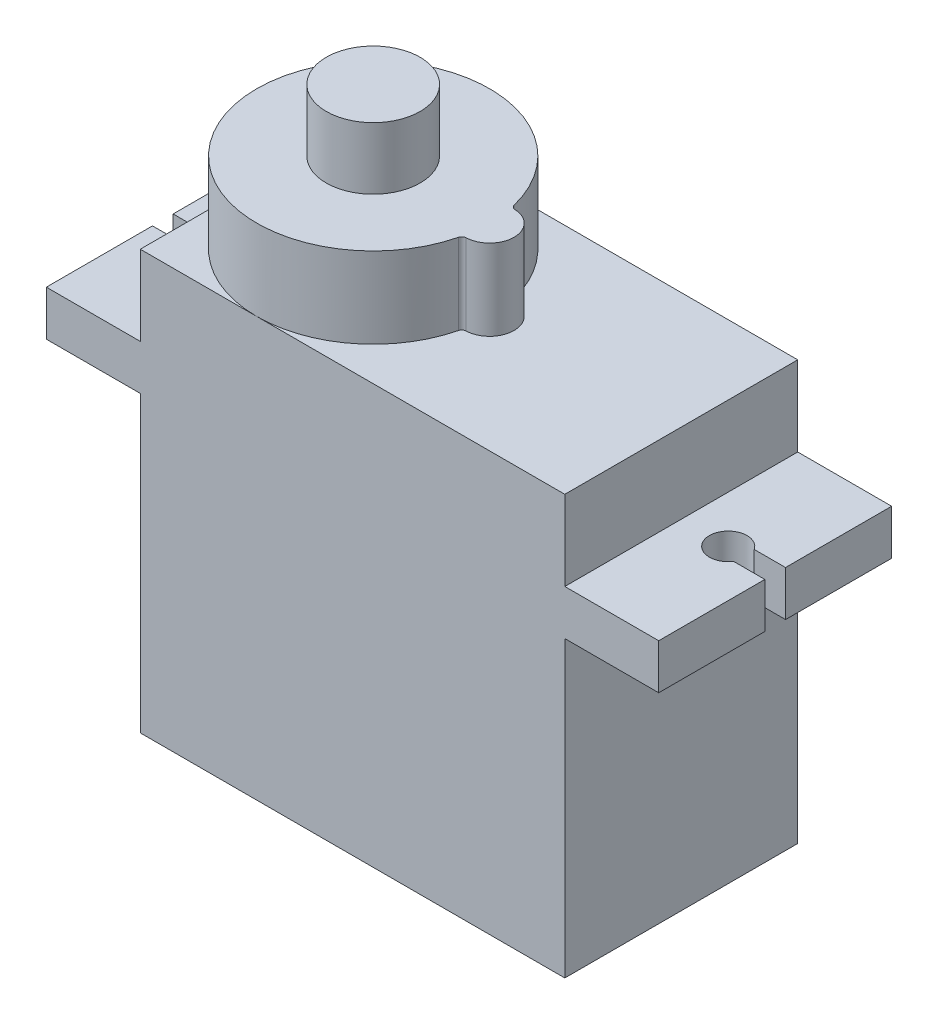
SolidWorks part; units mm, degrees
ref_plane "Front Plane" through (0, 0, 0) normal (0, 0, 1) x (1, 0, 0)
ref_plane "Top Plane" through (0, 0, 0) normal (0, 1, 0) x (1, 0, 0)
ref_plane "Right Plane" through (0, 0, 0) normal (1, 0, 0) x (0, 0, -1)
sketch "Sketch1" plane through (0, 0, 0) normal (0, 1, 0) x (1, 0, 0)
  line L1 (-11.3, 6.2) -> (11.3, 6.2)
  line L2 (-11.3, 6.2) -> (-11.3, -6.2)
  line L3 (-11.3, -6.2) -> (11.3, -6.2)
  line L4 (11.3, 6.2) -> (11.3, -6.2)
  line L5 (-11.3, 6.2) -> (11.3, -6.2) construction
  line L6 (-11.3, -6.2) -> (11.3, 6.2) construction
  point P0 (0, 0)
  dimension "D1" = 22.6
  dimension "D2" = 12.4
extrude "Boss-Extrude1" add sketch "Sketch1" along normal blind 22.3
sketch "Sketch2" plane through (0, 0, 6.2) normal (0, 0, 1) x (1, 0, 0)
  line L0 (11.3, 22.3) -> (11.3, 0) construction
  line L1 (16.3, 18.05) -> (11.3, 18.05)
  line L2 (16.3, 18.05) -> (16.3, 15.65)
  line L3 (16.3, 15.65) -> (11.3, 15.65)
  line L4 (11.3, 18.05) -> (11.3, 15.65)
  line L5 (16.3, 18.05) -> (11.3, 15.65) construction
  line L6 (16.3, 15.65) -> (11.3, 18.05) construction
  line L7 (-11.3, 22.3) -> (11.3, 22.3) construction
  line L8 (0, 0) -> (0, 14.975) construction
  line L9 (-16.3, 15.65) -> (-11.3, 18.05) construction
  line L10 (-16.3, 18.05) -> (-11.3, 15.65) construction
  line L11 (-11.3, 18.05) -> (-11.3, 15.65)
  line L12 (-16.3, 15.65) -> (-11.3, 15.65)
  line L13 (-16.3, 18.05) -> (-16.3, 15.65)
  line L14 (-16.3, 18.05) -> (-11.3, 18.05)
  point P0 (13.8, 16.85)
  point P16 (-13.8, 16.85)
  dimension "D1" = 4.25
  dimension "D2" = 2.4
  dimension "D3" = 5
extrude "Boss-Extrude2" add sketch "Sketch2" against normal up to vertex (12.4 mm away)
sketch "Sketch3" plane through (0, 18.05, 0) normal (0, 1, 0) x (1, 0, 0)
  line L0 (0, 0) -> (0, 25.3314) construction
  line L1 (0, 0) -> (13.8, 0) construction
  line L2 (14.6352, 0.55) -> (16.3, 0.55)
  line L3 (16.3, 6.2) -> (16.3, -6.2) construction
  line L4 (16.3, 0.55) -> (16.3, -0.55)
  line L5 (16.3, -0.55) -> (14.6352, -0.55)
  line L6 (-16.3, -0.55) -> (-14.6352, -0.55)
  line L7 (-16.3, 0.55) -> (-16.3, -0.55)
  line L8 (-14.6352, 0.55) -> (-16.3, 0.55)
  arc A0 (14.6352, 0.55) -> (14.6352, -0.55) centre (13.8, 0) ccw
  arc A1 (-14.6352, 0.55) -> (-14.6352, -0.55) centre (-13.8, 0) cw
  dimension "D1" = 2.5
  dimension "D3" = 2
  dimension "D2" = 1.1
extrude "Cut-Extrude1" cut sketch "Sketch3" against normal through all
sketch "Sketch4" plane through (0, 22.3, 0) normal (0, 1, 0) x (1, 0, 0)
  line L0 (-11.3, 6.2) -> (-11.3, -6.2) construction
  line L1 (11.3, 6.2) -> (-11.3, 6.2) construction
  arc A0 (0.9186, 1.4888) -> (0.9186, -1.4888) centre (-5.1, 0) ccw
  arc A1 (1.1514, -1.299) -> (1.1514, 1.299) centre (1.1, 0) ccw
  arc A2 (1.1514, -1.299) -> (0.9186, -1.4888) centre (1.1613, -1.5488) ccw
  arc A3 (1.1514, 1.299) -> (0.9186, 1.4888) centre (1.1613, 1.5488) cw
  dimension "D1" = 12.4
  dimension "D2" = 2.6
  dimension "D3" = 0.25
extrude "Boss-Extrude3" add sketch "Sketch4" along normal blind 4.3
sketch "Sketch5" plane through (0, 26.6, 0) normal (0, 1, 0) x (1, 0, 0)
  circle A0 centre (-5.1, 0) radius 2.5
  dimension "D1" = 5
extrude "Boss-Extrude4" add sketch "Sketch5" along normal blind 3.3
sketch "Sketch6" plane through (-11.3, 0, 0) normal (-1, 0, 0) x (0, 0, 1)
  line L0 (0, 4.5) -> (0, 0) construction
  circle A0 centre (0, 4.5) radius 0.6
  circle A1 centre (1.2, 4.5) radius 0.6
  circle A2 centre (-1.2, 4.5) radius 0.6
  dimension "D1" = 1.2
  dimension "D2" = 4.5
extrude "Boss-Extrude7" add sketch "Sketch6" along normal blind 2.3 separate body
